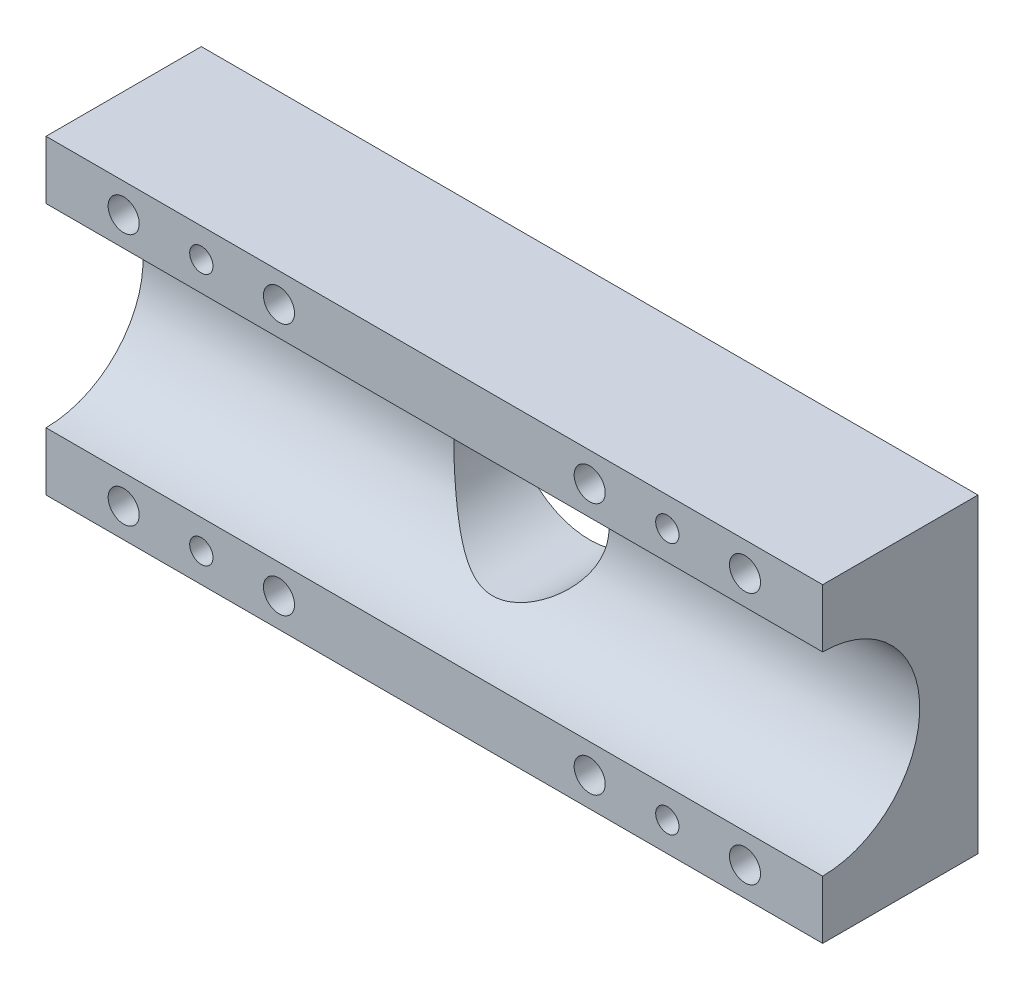
SolidWorks part; units mm, degrees
ref_plane "Front Plane" through (0, 0, 0) normal (0, 0, 1) x (1, 0, 0)
ref_plane "Top Plane" through (0, 0, 0) normal (0, 1, 0) x (1, 0, 0)
ref_plane "Right Plane" through (0, 0, 0) normal (1, 0, 0) x (0, 0, -1)
sketch "Sketch1" plane through (0, 0, 0) normal (0, 0, 1) x (1, 0, 0)
  line L1 (-50, 20) -> (50, 20)
  line L2 (-50, 20) -> (-50, -20)
  line L3 (-50, -20) -> (50, -20)
  line L4 (50, 20) -> (50, -20)
  line L5 (-50, 20) -> (50, -20) construction
  line L6 (-50, -20) -> (50, 20) construction
  point P0 (0, 0)
extrude "Boss-Extrude2" add sketch "Sketch1" along normal blind 20
sketch "Sketch3" plane through (50, 0, 0) normal (1, 0, 0) x (0, 0, -1)
  line L0 (-20, -20) -> (-20, 20) construction
  circle A0 centre (-20, 0) radius 12.5
extrude "Cut-Extrude1" cut sketch "Sketch3" against normal blind 100
sketch "Sketch4" plane through (0, 0, 20) normal (0, 0, 1) x (1, 0, 0)
  line L0 (47.4694, 20) -> (47.4694, 12.5)
  line L1 (50, 20) -> (-50, 20) construction
  line L2 (50, 12.5) -> (-50, 12.5) construction
  line L3 (50, 16.25) -> (40, 16.25)
  line L4 (50, 12.5) -> (50, 20) construction
  line L5 (-50, 16.25) -> (-40, 16.25)
  line L6 (-50, 20) -> (-50, 12.5) construction
  line L7 (-38, 16.25) -> (-30, 16.25)
  line L8 (-28.5, 16.25) -> (-20, 16.25)
  line L9 (38, 16.25) -> (30, 16.25)
  circle A0 centre (40, 16.25) radius 2
  circle A1 centre (-40, 16.25) radius 2
  circle A2 centre (-30, 16.25) radius 1.5
  circle A3 centre (-20, 16.25) radius 2
  circle A4 centre (30, 16.25) radius 1.5
  circle A5 centre (20, 16.25) radius 2
  circle A6 centre (-40, -16.25) radius 2
  circle A7 centre (-30, -16.25) radius 1.5
  circle A8 centre (-20, -16.25) radius 2
  circle A9 centre (20, -16.25) radius 2
  circle A10 centre (30, -16.25) radius 1.5
  circle A11 centre (40, -16.25) radius 2
extrude "Cut-Extrude2" cut sketch "Sketch4" against normal blind 20
sketch "Sketch5" plane through (0, 0, 0) normal (0, 0, -1) x (-1, 0, 0)
  circle A0 centre (0, 0) radius 10
extrude "Cut-Extrude3" cut sketch "Sketch5" against normal blind 20
